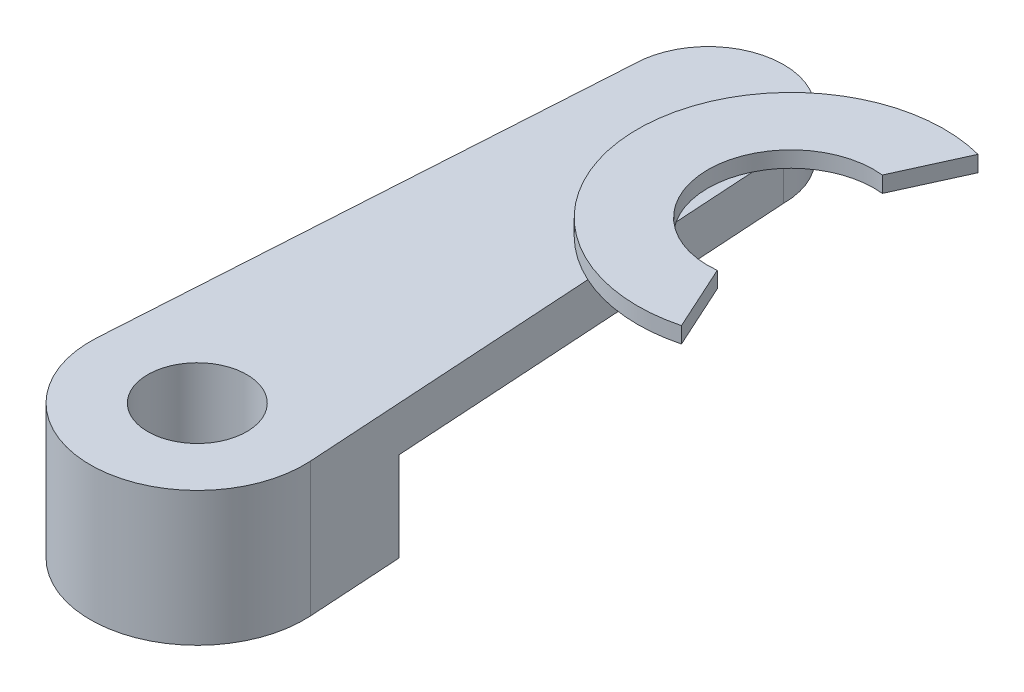
SolidWorks part; units mm, degrees
ref_plane "Front Plane" through (0, 0, 0) normal (0, 0, 1) x (1, 0, 0)
ref_plane "Top Plane" through (0, 0, 0) normal (0, 1, 0) x (1, 0, 0)
ref_plane "Right Plane" through (0, 0, 0) normal (1, 0, 0) x (0, 0, -1)
sketch "Sketch1" plane through (0, 0, 0) normal (0, 1, 0) x (1, 0, 0)
  line L0 (-3.3435, 0.2079) -> (-2.3614, 16)
  line L1 (0, 0) -> (0, 16) construction
  line L2 (3.3435, 0.2079) -> (2.3614, 16)
  circle A0 centre (0, 0) radius 3.35
  arc A1 (-2.3614, 16) -> (2.3614, 16) centre (0, 16) cw
  dimension "D1" = 6.7
  dimension "D2" = 16
extrude "Boss-Extrude1" add sketch "Sketch1" along normal blind 4.2
sketch "Sketch2" plane through (0, 4.2, 0) normal (0, 1, 0) x (1, 0, 0)
  circle A0 centre (0, 0) radius 1.55
extrude "Cut-Extrude1" cut sketch "Sketch2" against normal blind 4.2
sketch "Sketch3" plane through (0, 4.2, 0) normal (0, 1, 0) x (1, 0, 0)
  line L1 (5.9788, 9.1832) -> (5.041, 11.2416)
  line L2 (5.0395, 16.4121) -> (5.9763, 18.471)
  arc A0 (5.9788, 9.1832) -> (5.9763, 18.471) centre (4.7635, 13.8268) cw
  arc A1 (5.041, 11.2416) -> (5.0395, 16.4121) centre (4.7635, 13.8268) cw
  dimension "D1" = 2.6
  dimension "D2" = 4.8
extrude "Washer" add sketch "Sketch3" along normal blind 0.5 contours L2 A0 L1 A1
sketch "Sketch4" plane through (0, 0, 0) normal (0, -1, 0) x (-1, 0, 0)
  line L1 (-7.7715, 21.9847) -> (7.2429, 21.9847)
  line L2 (-7.7715, 21.9847) -> (-7.7715, 3.1544)
  line L3 (-7.7715, 3.1544) -> (7.2429, 3.1544)
  line L4 (7.2429, 21.9847) -> (7.2429, 3.1544)
extrude "Cut-Extrude2" cut sketch "Sketch4" against normal offset from surface (2.8 mm away) 1.4 up to face at (0, 4.2, 1.55)
